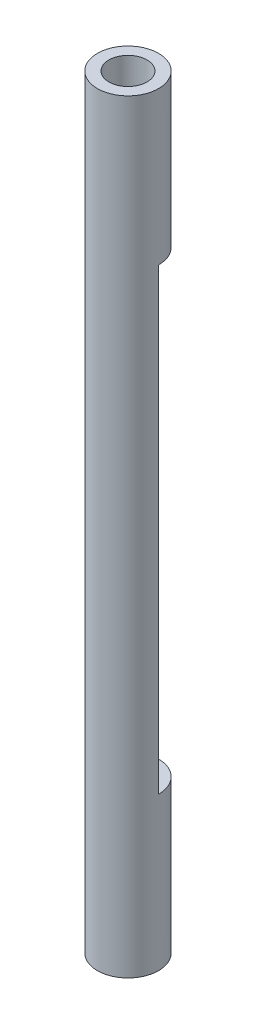
SolidWorks part; units mm, degrees
ref_plane "前视基准面" through (0, 0, 0) normal (0, 0, 1) x (1, 0, 0)
ref_plane "上视基准面" through (0, 0, 0) normal (0, 1, 0) x (1, 0, 0)
ref_plane "右视基准面" through (0, 0, 0) normal (1, 0, 0) x (0, 0, -1)
other "Configuration Table"
sketch "草图1" plane through (0, 0, 0) normal (0, 1, 0) x (1, 0, 0)
  circle A0 centre (0, 0) radius 4
  circle A1 centre (0, 0) radius 2.5
  dimension "D1" = 5
  dimension "D2" = 8
extrude "凸台-拉伸1" add sketch "草图1" along normal blind 100
sketch "草图2" plane through (0, 0, 0) normal (1, 0, 0) x (0, 0, -1)
  line L0 (0, -1000) -> (0, 49000) construction
  line L1 (4, 0) -> (4, 100) construction
  line L2 (8, 20) -> (0, 20)
  line L3 (8, 20) -> (8, 80)
  line L4 (8, 80) -> (0, 80)
  line L5 (0, 20) -> (0, 80)
  line L6 (8, 20) -> (0, 80) construction
  line L7 (8, 80) -> (0, 20) construction
  point P1 (4, 50)
  dimension "D1" = 60
extrude "切除-拉伸1" cut sketch "草图2" against normal through all and the other way through all
